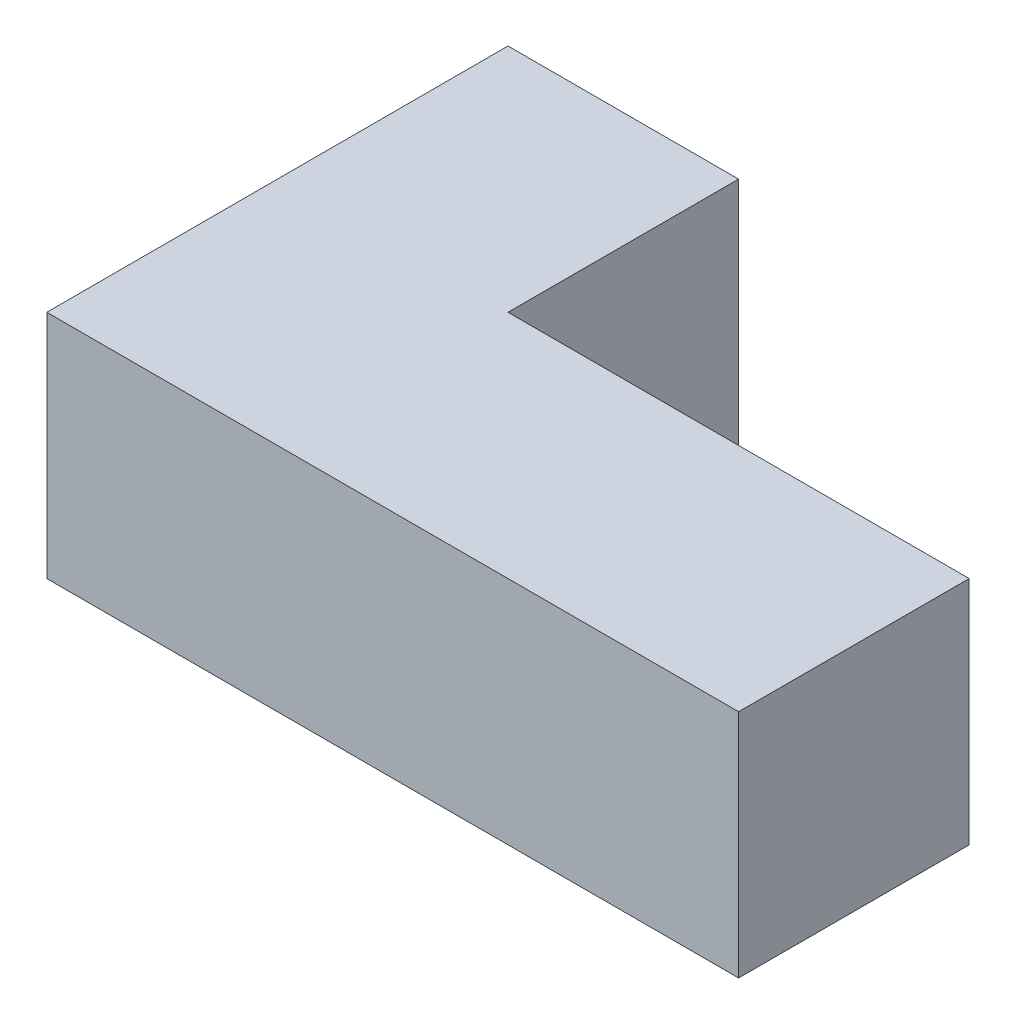
SolidWorks part; units mm, degrees
ref_plane "前基準面" through (0, 0, 0) normal (0, 0, 1) x (1, 0, 0)
ref_plane "上基準面" through (0, 0, 0) normal (0, 1, 0) x (1, 0, 0)
ref_plane "右基準面" through (0, 0, 0) normal (1, 0, 0) x (0, 0, -1)
sketch "草圖1" plane through (0, 0, 0) normal (0, 1, 0) x (1, 0, 0)
  line L1 (0, 0) -> (60, 0)
  line L2 (0, 0) -> (0, 30)
  line L3 (0, 30) -> (60, 30)
  line L4 (60, 0) -> (60, 30)
  line L5 (0, 30) -> (30, 30)
  line L6 (0, 30) -> (0, 60)
  line L7 (0, 60) -> (30, 60)
  line L8 (30, 30) -> (30, 60)
  dimension "D1" = 30
  dimension "D2" = 60
  dimension "D3" = 30
  dimension "D4" = 30
extrude "填料-伸長1" add sketch "草圖1" along normal blind 30 contours L1 L4 L3 L2 | L3 L8 L7 L6
sketch "草圖3" plane through (60, 0, 0) normal (1, 0, 0) x (0, 0, -1)
  line L4 (0, 0) -> (30, 0)
  line L5 (30, 0) -> (30, 30)
  line L6 (30, 30) -> (0, 30)
  line L7 (0, 30) -> (0, 0)
  line L8 (0, 0) -> (30, 0)
  line L9 (30, 0) -> (30, 30)
  line L10 (30, 30) -> (0, 30)
  line L11 (0, 30) -> (0, 0)
  dimension "D1" = 0
extrude "填料-伸長3" add sketch "草圖3" along normal blind 30
